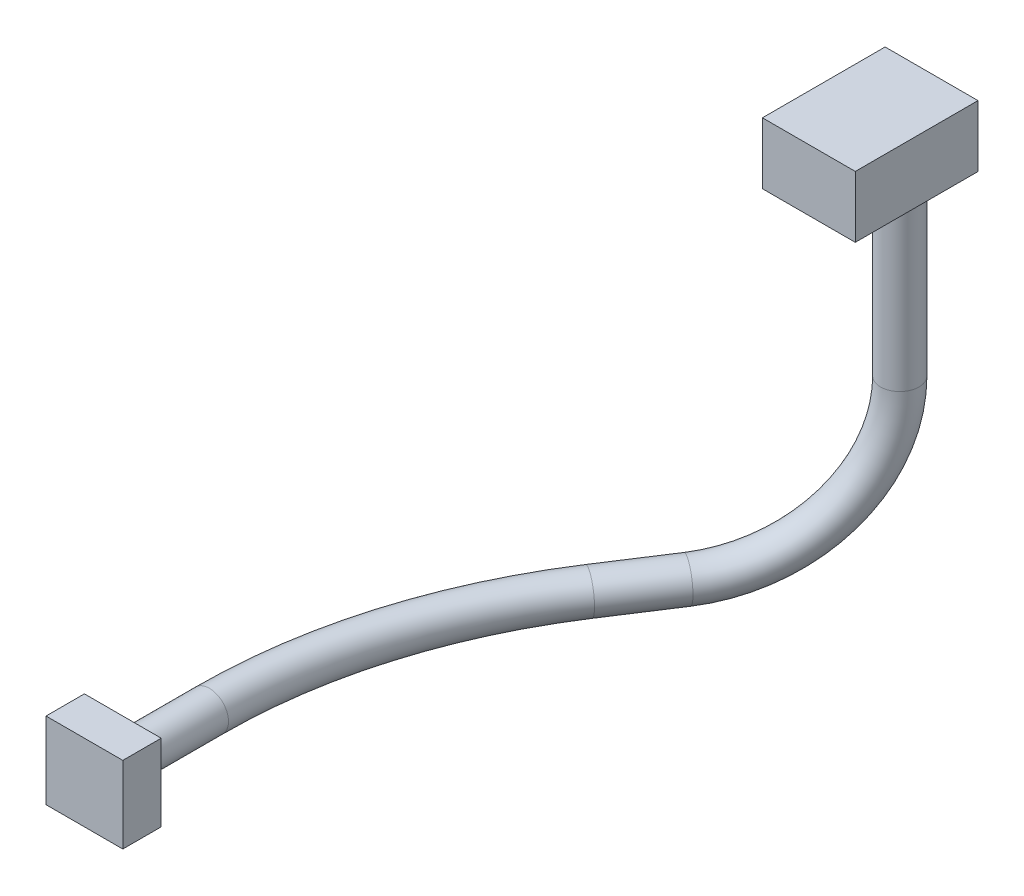
SolidWorks part; units mm, degrees
ref_plane "前视基准面" through (0, 0, 0) normal (0, 0, 1) x (1, 0, 0)
ref_plane "上视基准面" through (0, 0, 0) normal (0, 1, 0) x (1, 0, 0)
ref_plane "右视基准面" through (0, 0, 0) normal (1, 0, 0) x (0, 0, -1)
sketch "草图10" plane through (0, 0, 0) normal (0, 0, 1) x (1, 0, 0)
  line L1 (-5, 5) -> (5, 5)
  line L2 (-5, 5) -> (-5, -5)
  line L3 (-5, -5) -> (5, -5)
  line L4 (5, 5) -> (5, -5)
  line L5 (-5, 5) -> (5, -5) construction
  line L6 (-5, -5) -> (5, 5) construction
  point P0 (0, 0)
  dimension "D1" = 10
sketch3d "3D草图1"
  line L0 (0, 0, 0) -> (0, 0, -11.2651)
  line L1 (11.2931, 0, -49.3898) -> (16.3392, 0, -57.1601)
  line L2 (27.232, 20, -73.9335) -> (27.232, 44, -73.9335)
  arc A0 (11.2931, 0, -49.3898) -> (0, 0, -11.2651) centre (70, 0, -11.2651) ccw
  arc A1 (27.232, 20, -73.9335) -> (16.3392, 0, -57.1601) centre (16.3392, 20, -57.1601) ccw
  point P7 (0, 0, -32)
  point P9 (70, 70, -11.2651)
  point P12 (27.232, 0, -73.9335)
  point P13 (-0.4342, 20, -68.0529)
  dimension "D2" = 70
  dimension "D3" = 20
  dimension "D1" = 147
  dimension "D4" = 50
  dimension "D5" = 44
  dimension "D6" = 32
sweep "扫描1" add path "3D草图1" circular profile diameter 5 parameters "D3"=5
extrude "凸台-拉伸1" add sketch "草图10" along normal blind 5
sketch "草图11" plane through (0, 44, 0) normal (0, 1, 0) x (1, 0, 0)
  line L0 (27.232, 73.9335) -> (27.232, 78.0705) construction
  line L1 (21.1852, 78.0705) -> (33.2787, 78.0705)
  line L2 (21.1852, 78.0705) -> (21.1852, 62.0943)
  line L3 (21.1852, 62.0943) -> (33.2787, 62.0943)
  line L4 (33.2787, 78.0705) -> (33.2787, 62.0943)
  circle A0 centre (27.232, 73.9335) radius 2.5 construction
extrude "凸台-拉伸2" add sketch "草图11" along normal blind 8
